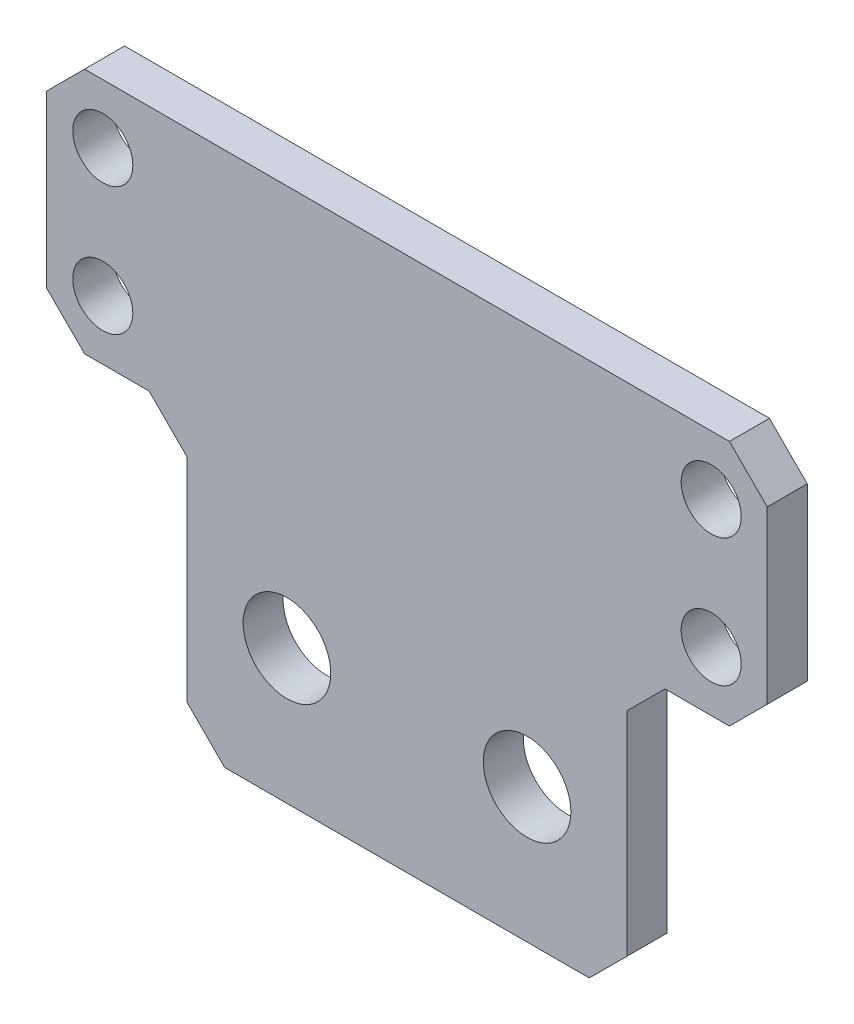
SolidWorks part; units mm, degrees
ref_plane "Front Plane" through (0, 0, 0) normal (0, 0, 1) x (1, 0, 0)
ref_plane "Top Plane" through (0, 0, 0) normal (0, 1, 0) x (1, 0, 0)
ref_plane "Right Plane" through (0, 0, 0) normal (1, 0, 0) x (0, 0, -1)
sketch "Sketch1" plane through (0, 0, 0) normal (0, 0, 1) x (1, 0, 0)
  line L0 (-17.4625, -10.541) -> (17.4625, -10.541) construction
  line L1 (17.4625, -21.209) -> (-17.4625, -21.209)
  line L2 (17.4625, -21.209) -> (17.4625, 1.651)
  line L3 (17.4625, 21.209) -> (-17.4625, 21.209)
  line L4 (-17.4625, -21.209) -> (-17.4625, 1.651)
  line L5 (17.4625, -21.209) -> (-17.4625, 21.209) construction
  line L6 (17.4625, 21.209) -> (-17.4625, -21.209) construction
  line L7 (0, 21.209) -> (0, -21.209) construction
  line L8 (-17.4625, 1.651) -> (17.4625, 1.651) construction
  line L9 (-17.4625, 6.35) -> (17.4625, 6.35) construction
  line L10 (-17.4625, 11.43) -> (17.4625, 11.43) construction
  line L11 (-17.4625, 11.43) -> (-17.4625, 1.651) construction
  line L12 (-17.4625, 5.4539) -> (-17.4625, 6.35)
  line L13 (28.575, 1.651) -> (17.4625, 1.651)
  line L14 (28.575, 1.651) -> (28.575, 21.209)
  line L15 (28.575, 21.209) -> (-28.575, 21.209)
  line L16 (-28.575, 1.651) -> (-28.575, 21.209)
  line L17 (28.575, 1.651) -> (-28.575, 21.209) construction
  line L18 (28.575, 21.209) -> (-28.575, 1.651) construction
  line L19 (17.4625, 5.4539) -> (17.4625, 6.35)
  line L20 (1.3594, 1.651) -> (-1.3594, 1.651)
  line L21 (-17.4625, 1.651) -> (-28.575, 1.651)
  circle A0 centre (-9.525, -10.541) radius 3.475
  circle A1 centre (9.525, -10.541) radius 3.475
  circle A2 centre (-24.13, 6.35) radius 2.3828
  circle A3 centre (-24.13, 16.51) radius 2.3828
  circle A4 centre (24.13, 16.51) radius 2.3828
  circle A5 centre (24.13, 6.35) radius 2.3828
  point P0 (0, 0)
  point P28 (0, 11.43)
  dimension "D4" = 9.525
  dimension "D7" = 9.779
  dimension "D1" = 34.925
  dimension "D2" = 42.418
  dimension "D3" = 10.668
  dimension "D5" = 22.86
  dimension "D6" = 4.699
  dimension "D8" = 24.13
  dimension "D9" = 57.15
extrude "Boss-Extrude1" add sketch "Sketch1" along normal blind 3.175
chamfer "Chamfer1" distance 3 angle 45 4 edges at (28.575, 21.209, 1.5875) (28.575, 1.651, 1.5875) (-28.575, 1.651, 1.5875) (-28.575, 21.209, 1.5875)
chamfer "Chamfer2" distance 3 angle 45 4 edges at (-17.4625, 1.651, 1.5875) (-17.4625, -21.209, 1.5875) (17.4625, 1.651, 1.5875) (17.4625, -21.209, 1.5875)
